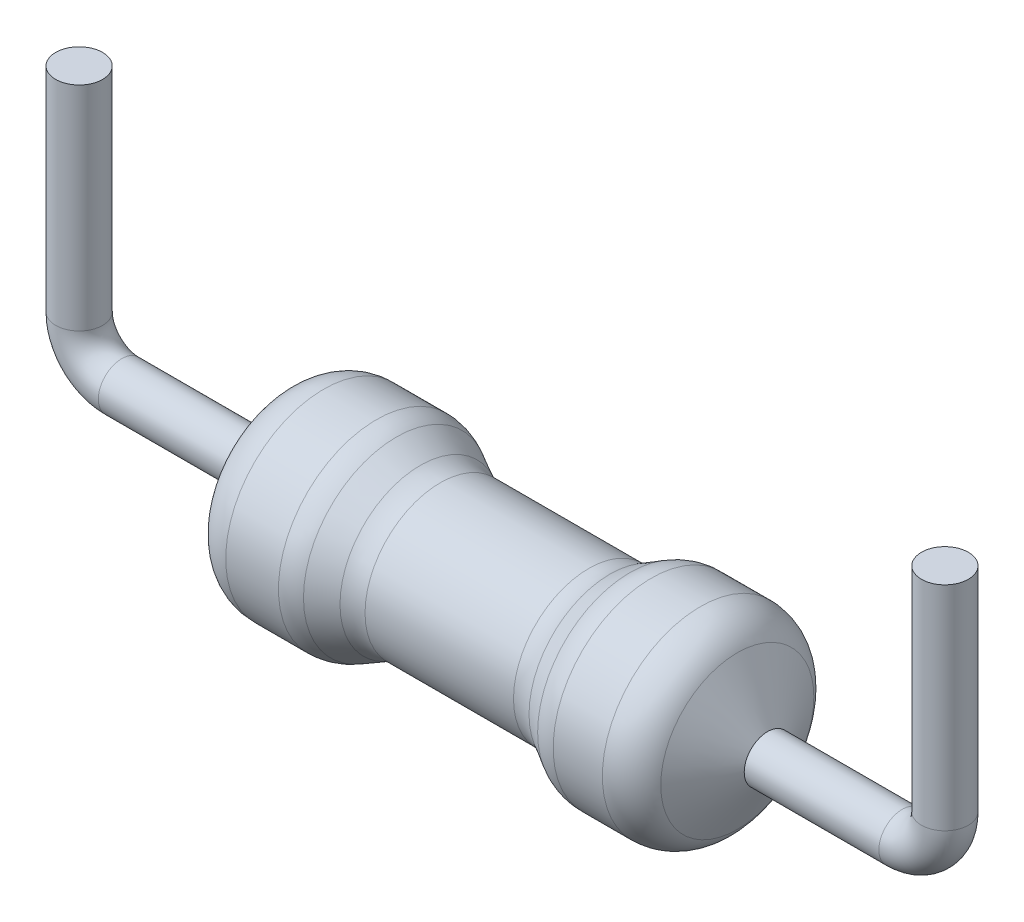
SolidWorks part; units mm, degrees
ref_plane "Front Plane" through (0, 0, 0) normal (0, 0, 1) x (1, 0, 0)
ref_plane "Top Plane" through (0, 0, 0) normal (0, 1, 0) x (1, 0, 0)
ref_plane "Right Plane" through (0, 0, 0) normal (1, 0, 0) x (0, 0, -1)
sketch "Sketch1" plane through (0, 0, 0) normal (0, 0, 1) x (1, 0, 0)
  line L0 (0, 0) -> (3, 0)
  line L1 (3, 0) -> (3, 0.275)
  line L2 (3, 0.275) -> (2.5, 1.15)
  line L3 (2.5, 1.15) -> (1.5, 1.15)
  line L4 (1.5, 1.15) -> (1.0338, 0.8836)
  line L5 (1.0338, 0.8836) -> (-0.9662, 0.8836)
  line L6 (-0.9662, 0.8836) -> (-1.4662, 1.15)
  line L7 (-1.4662, 1.15) -> (-2.5, 1.15)
  line L8 (-2.5, 1.15) -> (-3, 0.275)
  line L9 (-3, 0.275) -> (-3, 0)
  line L10 (-3, 0) -> (0, 0)
  point P2 (2, 1.15)
  dimension "D1" = 0.275
  dimension "D2" = 0.275
  dimension "D3" = 3
  dimension "D4" = 3
  dimension "D5" = 1.15
  dimension "D6" = 1.15
  dimension "D7" = 0.5
  dimension "D8" = 0.5
  dimension "D9" = 1
  dimension "D10" = 1.0338
  dimension "D11" = 2
  dimension "D12" = 0.5
  dimension "D13" = 0.8836
revolve "Revolve1" add sketch "Sketch1" angle 360 about L0
fillet "Fillet1" radius 0.5 6 edges at (-2.5, 0, 1.15) (-1.4662, 0, 1.15) (-0.9662, 0, 0.8836) (1.0338, 0, 0.8836) (1.5, 0, 1.15) (2.5, 0, 1.15)
sketch "Sketch4" plane through (3, 0, 0) normal (1, 0, 0) x (0, 0, -1)
  circle A0 centre (0, 0) radius 0.275
sketch "Sketch6" plane through (0, 0, 0) normal (0, 0, 1) x (1, 0, 0)
  line L0 (3, 0) -> (4.58, 0)
  line L1 (5.08, 0.5) -> (5.08, 3)
  line L2 (3, 0) -> (-4.58, 0)
  line L3 (-5.08, 0.5) -> (-5.08, 3)
  arc A0 (-4.58, 0) -> (-5.08, 0.5) centre (-4.58, 0.5) cw
  arc A1 (4.58, 0) -> (5.08, 0.5) centre (4.58, 0.5) ccw
  point P8 (-5.08, 0)
  point P11 (5.08, 0)
  dimension "D5" = 0.5
  dimension "D1" = 2.08
  dimension "D2" = 3
  dimension "D3" = 8.08
  dimension "D4" = 3
sweep "Sweep1" add profiles "Sketch4" path "Sketch6"
